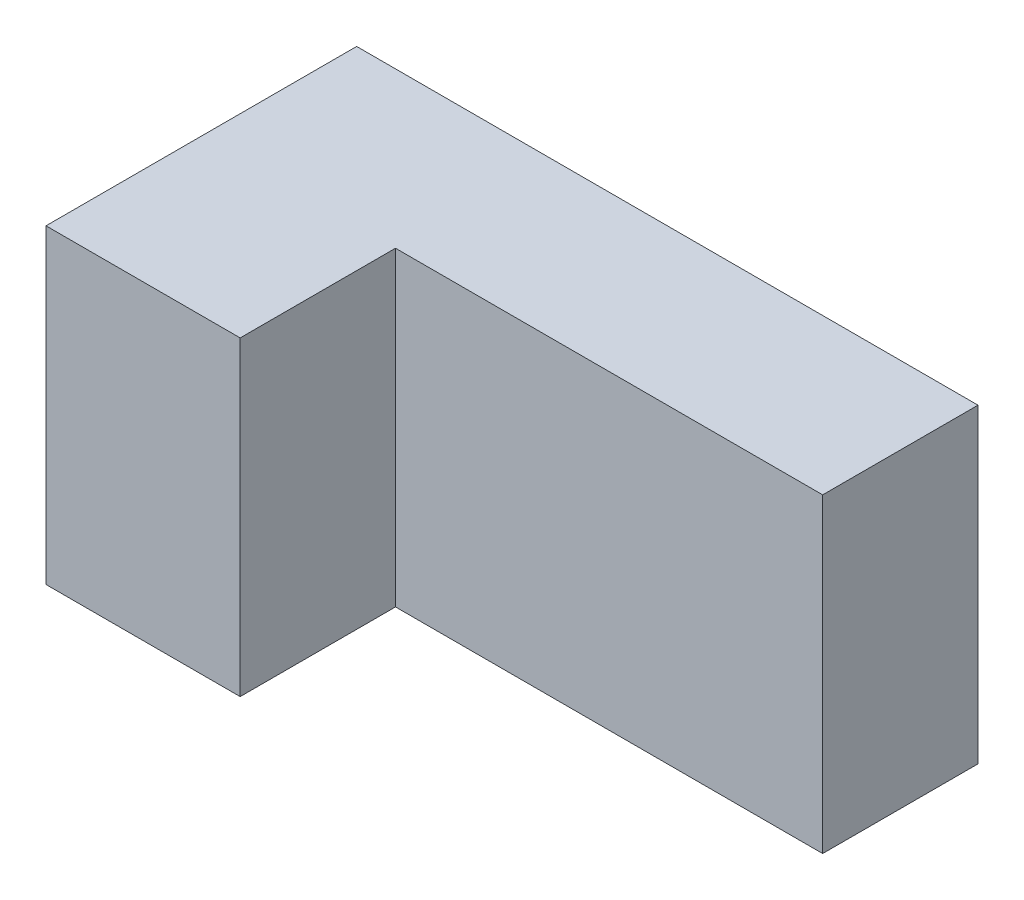
SolidWorks part; units mm, degrees
ref_plane "前视基准面" through (0, 0, 0) normal (0, 0, 1) x (1, 0, 0)
ref_plane "上视基准面" through (0, 0, 0) normal (0, 1, 0) x (1, 0, 0)
ref_plane "右视基准面" through (0, 0, 0) normal (1, 0, 0) x (0, 0, -1)
sketch "草图1" plane through (0, 0, 0) normal (0, 0, 1) x (1, 0, 0)
  line L1 (-40, -20) -> (40, -20)
  line L2 (-40, -20) -> (-40, 20)
  line L3 (-40, 20) -> (40, 20)
  line L4 (40, -20) -> (40, 20)
  line L5 (-40, -20) -> (40, 20) construction
  line L6 (-40, 20) -> (40, -20) construction
  point P0 (0, 0)
extrude "凸台-拉伸1" add sketch "草图1" along normal blind 20
sketch "草图2" plane through (0, 0, 20) normal (0, 0, 1) x (1, 0, 0)
  line L0 (-40, -20) -> (40, -20) construction
  line L1 (-40, 20) -> (-15, 20)
  line L2 (-40, 20) -> (-40, -20)
  line L3 (-40, -20) -> (-15, -20)
  line L4 (-15, 20) -> (-15, -20)
extrude "凸台-拉伸2" add sketch "草图2" along normal blind 20
sketch "草图3" plane through (-40, 0, 0) normal (-1, 0, 0) x (0, 0, 1)
  circle A0 centre (21.8582, 0) radius 9.5593
extrude "切除-拉伸1" cut sketch "草图3" against normal blind 5
